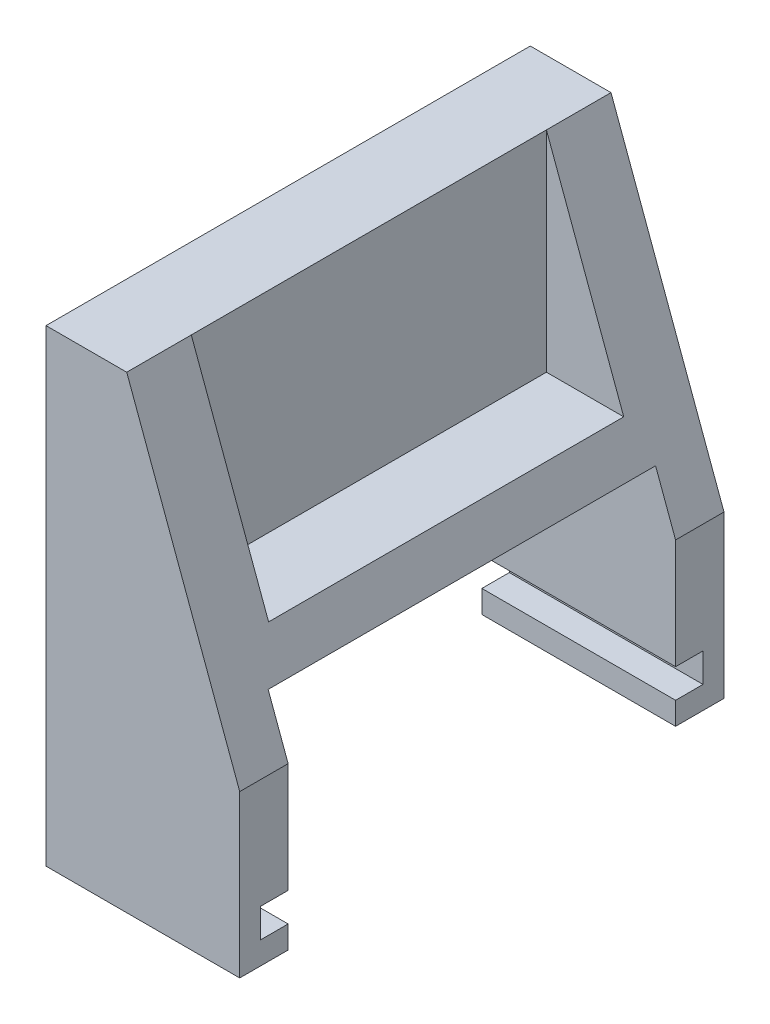
SolidWorks part; units mm, degrees
ref_plane "Front Plane" through (0, 0, 0) normal (0, 0, 1) x (1, 0, 0)
ref_plane "Top Plane" through (0, 0, 0) normal (0, 1, 0) x (1, 0, 0)
ref_plane "Right Plane" through (0, 0, 0) normal (1, 0, 0) x (0, 0, -1)
sketch "Sketch1" plane through (0, 0, 0) normal (0, 0, 1) x (1, 0, 0)
  line L0 (0, 0) -> (0, -29)
  line L1 (0, -29) -> (12, -29)
  line L2 (12, -29) -> (12, -19)
  line L3 (12, -19) -> (5, 0)
  line L4 (5, 0) -> (0, 0)
  dimension "D1" = 29
  dimension "D2" = 12
  dimension "D3" = 10
  dimension "D4" = 5
extrude "Boss-Extrude1" add sketch "Sketch1" against normal blind 30
sketch "Sketch4" plane through (0, 0, 0) normal (-1, 0, 0) x (0, 0, 1)
  line L0 (-30, 0) -> (-30, -29) construction
  line L1 (-27, -15.6386) -> (-3, -15.6386)
  line L2 (-27, -15.6386) -> (-27, -29.6386)
  line L3 (-27, -29.6386) -> (-3, -29.6386)
  line L4 (-3, -15.6386) -> (-3, -29.6386)
  point P4 (-27, -22.6386)
  dimension "D1" = 24
  dimension "D2" = 14
  dimension "D3" = 3
extrude "Cut-Extrude2" cut sketch "Sketch4" against normal blind 25 contours L2 L1 L4 L3
sketch "Sketch5" plane through (0, 0, 0) normal (-1, 0, 0) x (0, 0, 1)
  line L0 (-3, -15.6386) -> (-3, -29) construction
  line L1 (-3, -25.8) -> (-1.3, -25.8)
  line L2 (-3, -25.8) -> (-3, -27.6)
  line L3 (-3, -27.6) -> (-1.3, -27.6)
  line L4 (-1.3, -25.8) -> (-1.3, -27.6)
  line L5 (-3, -29) -> (0, -29) construction
  dimension "D1" = 1.8
  dimension "D2" = 1.7
  dimension "D3" = 1.4
extrude "Cut-Extrude3" cut sketch "Sketch5" against normal blind 15
ref_plane "Plane1" through (0, 0, -15) normal (0, 0, 1) x (1, 0, 0)
mirror "Mirror1" about plane through (0, 0, -15) normal (0, 0, 1) of "Cut-Extrude3"
sketch "Sketch6" plane through (0, 0, -15) normal (0, 0, 1) x (1, 0, 0)
  line L0 (5, 0) -> (5, -13)
  line L1 (5, -13) -> (9.7895, -13)
  line L2 (12, -19) -> (5, 0) construction
  line L3 (9.7895, -13) -> (5, 0)
  dimension "D1" = 13
extrude "Cut-Extrude4" cut sketch "Sketch6" against normal mid plane 22
